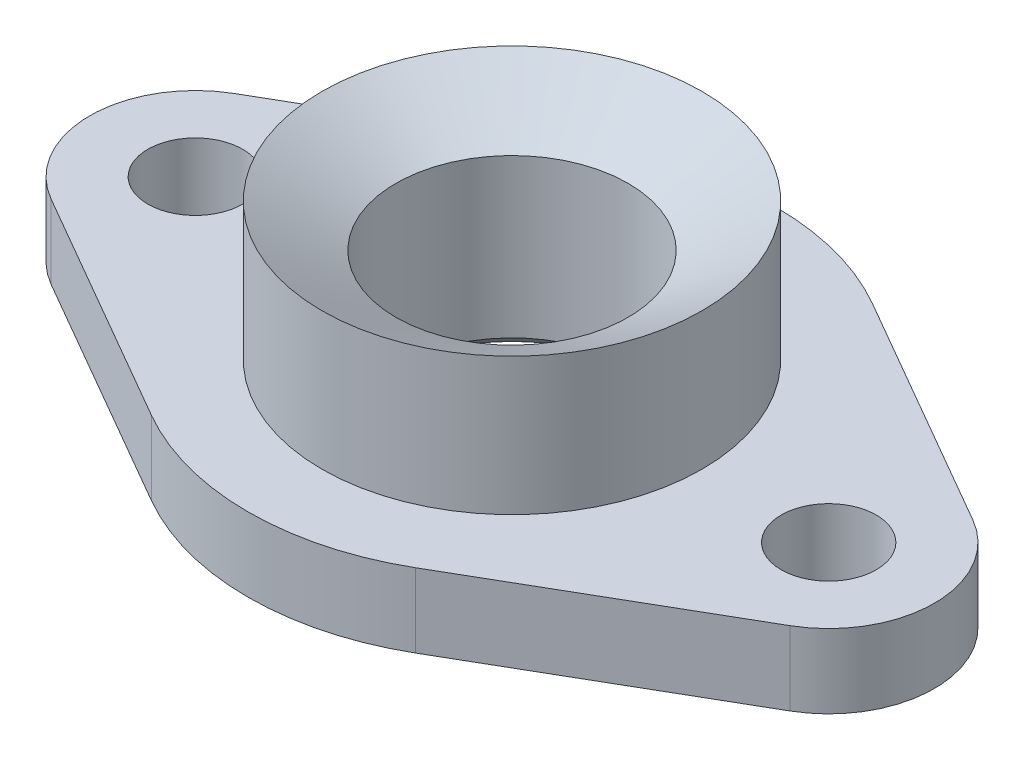
SolidWorks part; units mm, degrees
ref_plane "前视基准面" through (0, 0, 0) normal (0, 0, 1) x (1, 0, 0)
ref_plane "上视基准面" through (0, 0, 0) normal (0, 1, 0) x (1, 0, 0)
ref_plane "右视基准面" through (0, 0, 0) normal (1, 0, 0) x (0, 0, -1)
sketch "草图2" plane through (0, 0, 0) normal (0, 1, 0) x (1, 0, 0)
  line L0 (0, 55.4765) -> (0, -62.7389) construction
  line L1 (-81.9035, 0) -> (86.7451, 0) construction
  line L2 (-12.5, 21.6506) -> (-35, 8.6603)
  line L3 (-35, -8.6603) -> (-12.5, -21.6506)
  line L4 (12.5, 21.6506) -> (35, 8.6603)
  line L5 (12.5, -21.6506) -> (35, -8.6603)
  arc A0 (-12.5, -21.6506) -> (12.5, -21.6506) centre (0, 0) ccw
  circle A1 centre (-30, 0) radius 4.5
  circle A2 centre (30, 0) radius 4.5
  arc A3 (-35, 8.6603) -> (-35, -8.6603) centre (-30, 0) ccw
  arc A4 (35, 8.6603) -> (35, -8.6603) centre (30, 0) cw
  arc A5 (12.5, 21.6506) -> (-12.5, 21.6506) centre (0, 0) ccw
  dimension "D2" = 9
  dimension "D3" = 50
  dimension "D4" = 10
  dimension "D1" = 60
extrude "拉伸1" add sketch "草图2" along normal blind 7
sketch "草图3" plane through (0, 7, 0) normal (0, 1, 0) x (1, 0, 0)
  circle A0 centre (0, 0) radius 18
  dimension "D1" = 36
extrude "拉伸2" add sketch "草图3" along normal blind 13
sketch "草图4" plane through (0, 20, 0) normal (0, 0, -1) x (1, 0, 0)
  line L0 (0, 29.5758) -> (0, -8.5469) construction
  line L1 (0, 20) -> (11, 20)
  line L2 (12.5, 20) -> (-12.5, 20) construction
  line L3 (11, 20) -> (11, 4.0415)
  line L4 (11, 4.0415) -> (18, 0)
  line L5 (18, 0) -> (0, 0)
  line L6 (-18, 0) -> (18, 0) construction
  line L7 (0, 0) -> (0, 20)
  dimension "D1" = 22
  dimension "D2" = 60
revolve "切除-旋转2" cut sketch "草图4" angle 360 about L0
chamfer "倒角1" distance 1 angle 45 1 edges at (0, 0, -11)
